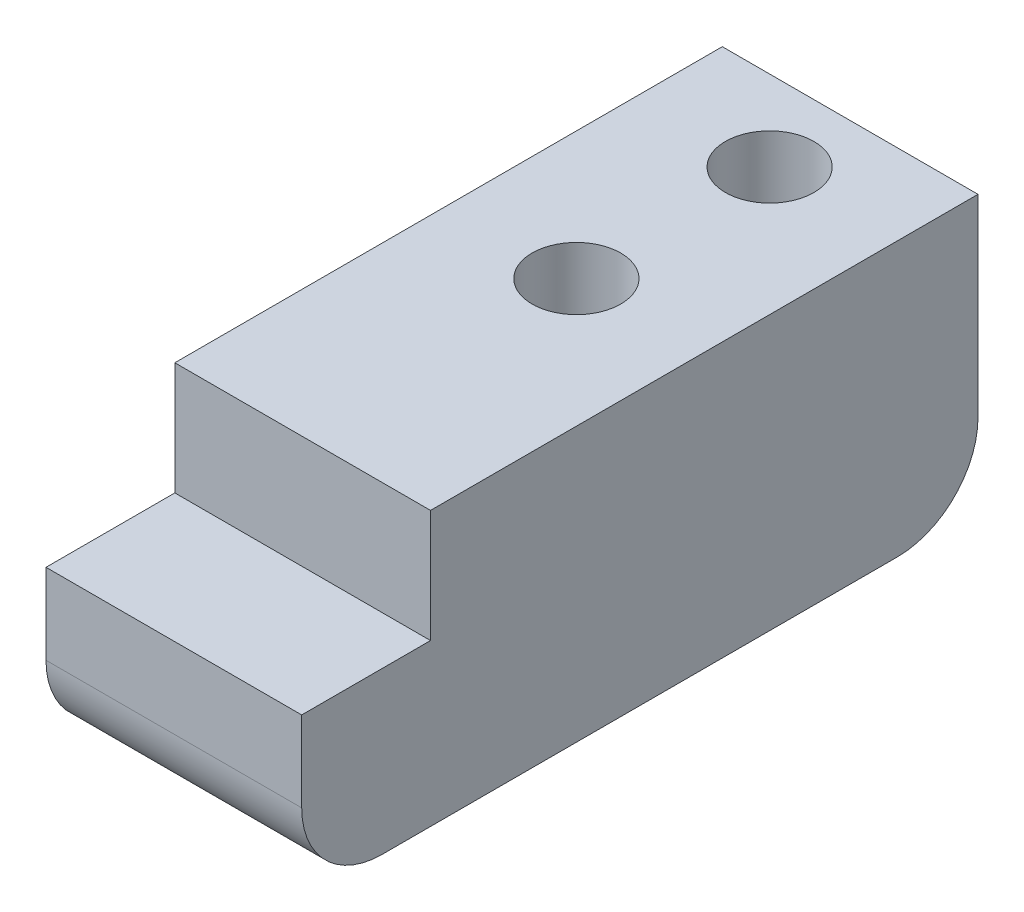
SolidWorks part; units mm, degrees
material "6063-T6"
ref_plane "Plano frontal" through (0, 0, 0) normal (0, 0, 1) x (1, 0, 0)
ref_plane "Plano superior" through (0, 0, 0) normal (0, 1, 0) x (1, 0, 0)
ref_plane "Plano direito" through (0, 0, 0) normal (1, 0, 0) x (0, 0, -1)
sketch "Esboço1" plane through (0, 0, 0) normal (1, 0, 0) x (0, 0, -1)
  line L1 (-17, -8.5) -> (17, -8.5)
  line L2 (-17, 1.5) -> (-17, 8.5)
  line L3 (-17, 8.5) -> (17, 8.5)
  line L4 (17, -8.5) -> (17, 8.5)
  line L5 (-17, -8.5) -> (17, 8.5) construction
  line L6 (-17, 8.5) -> (17, -8.5) construction
  line L7 (-17, -8.5) -> (-25, -8.5)
  line L9 (-17, 1.5) -> (-25, 1.5)
  line L10 (-25, -8.5) -> (-25, 1.5)
  point P0 (0, 0)
  dimension "D1" = 34
  dimension "D2" = 17
  dimension "D3" = 8
  dimension "D4" = 10
  dimension "D5" = 7
extrude "Ressalto-extrusão1" add sketch "Esboço1" along normal mid plane 15.88
fillet "Filete1" radius 5 2 edges at (0, -8.5, -17) (0, -8.5, 25)
hole_wizard "Escareado para SFHCS M51" positions "Esboço2" profile "Esboço3" countersink size "M5" standard "Ansi Metric"
sketch "Esboço2" plane through (-33.065, -8.5, -26.4602) normal (0, -1, 0) x (-1, 0, 0)
  line L5 (-33.065, -14.4602) -> (-33.065, -26.4602) construction
  line L6 (-33.065, -26.4602) -> (-33.065, -46.4602) construction
  line L8 (33.065, -46.4602) -> (33.065, -26.4602) construction
  line L10 (33.065, -26.4602) -> (33.065, -14.4602) construction
  point P12 (-33.065, -14.4602)
  point P22 (-33.065, -26.4602)
  point P38 (33.065, -26.4602)
  point P41 (33.065, -14.4602)
sketch "Esboço3" plane through (0, -8.5, -12) normal (1, 0, 0) x (0, 0, -1)
  line L0 (0, 0) -> (0, 31.6524)
  line L1 (0, 31.6524) -> (2.75, 30)
  line L2 (2.75, 30) -> (2.75, 3.35)
  line L3 (2.75, 3.35) -> (5.6, 0.5)
  line L4 (5.6, 0.5) -> (5.6, 0)
  line L5 (5.6, 0) -> (0, 0)
  line L6 (-2.75, 3.35) -> (-5.6, 0.5) construction
  line L7 (0, 31.6524) -> (-2.75, 30) construction
  line L8 (0, -6.35) -> (0, 107.95) construction
  dimension "Hole Dia." = 5.5
  dimension "Hole Depth" = 30
  dimension "C'Sink Dia." = 11.2
  dimension "C'Sink Angle" = 90
  dimension "Drill Angle" = 118
  dimension "Head Clearance" = 0.5
